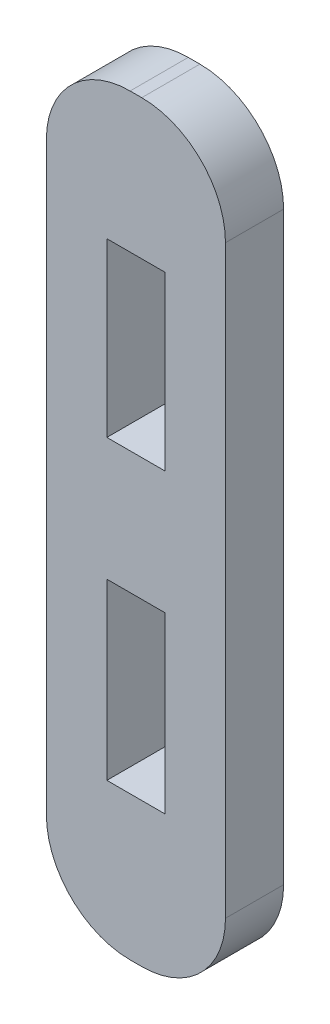
SolidWorks part; units mm, degrees
ref_plane "Front Plane" through (0, 0, 0) normal (0, 0, 1) x (1, 0, 0)
ref_plane "Top Plane" through (0, 0, 0) normal (0, 1, 0) x (1, 0, 0)
ref_plane "Right Plane" through (0, 0, 0) normal (1, 0, 0) x (0, 0, -1)
sketch "Sketch1" plane through (0, 0, 0) normal (0, 0, 1) x (1, 0, 0)
  line L0 (3.2385, 18.8942) -> (1.651, 18.8942) construction
  line L1 (0, 0) -> (4.8895, 0)
  line L2 (0, 0) -> (0, 20.5452)
  line L3 (0, 20.5452) -> (4.8895, 20.5452)
  line L4 (4.8895, 0) -> (4.8895, 20.5452)
  line L7 (3.2385, 16.7352) -> (3.2385, 18.8942) construction
  dimension "D1" = 1.651
  dimension "D2" = 1.651
extrude "Boss-Extrude1" add sketch "Sketch1" along normal blind 1.5875
sketch "Sketch2" plane through (0, 0, 0) normal (0, 0, -1) x (-1, 0, 0)
  line L1 (-3.2385, 14.1952) -> (-3.2385, 12.0362)
  line L2 (-3.2385, 12.0362) -> (-1.651, 12.0362)
  line L3 (-1.651, 12.0362) -> (-1.651, 14.1952)
  line L4 (-1.651, 15.6786) -> (-1.651, 18.5626) construction
  line L6 (-1.651, 16.7352) -> (-1.651, 18.8942) construction
  line L7 (-3.2385, 15.6786) -> (-3.2385, 18.5626) construction
  line L8 (-1.651, 5.2233) -> (-1.651, 6.4075) construction
  line L9 (-3.2385, 5.2233) -> (-3.2385, 4.8666) construction
  line L10 (-3.2385, 16.7352) -> (-1.651, 16.7352) construction
  line L11 (-3.2385, 6.4075) -> (-3.2385, 5.2233) construction
  line L12 (-1.651, 4.8666) -> (-1.651, 5.2233) construction
  line L13 (-1.651, 5.2233) -> (-1.651, 6.4075)
  line L14 (-1.651, 15.3514) -> (-1.651, 15.6786) construction
  line L15 (-1.651, 14.1952) -> (-1.651, 15.3514) construction
  line L16 (-3.2385, 16.7352) -> (-1.651, 16.7352)
  line L17 (-3.2385, 15.6786) -> (-3.2385, 15.3514) construction
  line L18 (-3.2385, 15.3514) -> (-3.2385, 14.1952) construction
  line L19 (-1.651, 15.6786) -> (-1.651, 16.7352)
  line L20 (-3.2385, 5.2233) -> (-3.2385, 4.8666)
  line L21 (-3.2385, 6.4075) -> (-3.2385, 5.2233)
  line L22 (-3.2385, 3.9278) -> (-1.651, 3.9278) construction
  line L25 (-3.2385, 15.6786) -> (-3.2385, 16.7352)
  line L26 (-1.651, 15.3514) -> (-1.651, 15.6786)
  line L27 (-1.651, 14.1952) -> (-1.651, 15.3514)
  line L28 (-3.2385, 15.6786) -> (-3.2385, 15.3514)
  line L29 (-3.2385, 3.9278) -> (-1.651, 3.9278)
  line L30 (-1.651, 4.8666) -> (-1.651, 5.2233)
  line L31 (-1.651, 1.9826) -> (-1.651, 4.8666) construction
  line L32 (-3.2385, 15.3514) -> (-3.2385, 14.1952)
  line L33 (-3.2385, 6.4075) -> (-3.2385, 8.6842)
  line L34 (-3.2385, 8.6842) -> (-1.651, 8.6842)
  line L35 (-1.651, 8.6842) -> (-1.651, 6.4075)
  line L36 (-1.651, 3.9278) -> (-1.651, 1.651) construction
  line L37 (-0.8554, 16.7352) -> (-0.8554, 18.8942) construction
  line L38 (-3.2385, 1.9826) -> (-3.2385, 4.8666) construction
  line L39 (-1.651, 3.9278) -> (-1.651, 4.8666)
  line L40 (-3.2385, 3.9278) -> (-3.2385, 4.8666)
  line L41 (-0.8554, 1.651) -> (-0.8554, 3.9278) construction
extrude "Cut-Extrude1" cut sketch "Sketch2" against normal through all
fillet "Fillet1" radius 2.286 4 edges at (0, 0, 0.7937) (4.8895, 0, 0.7937) (4.8895, 20.5452, 0.7937) (0, 20.5452, 0.7937)
